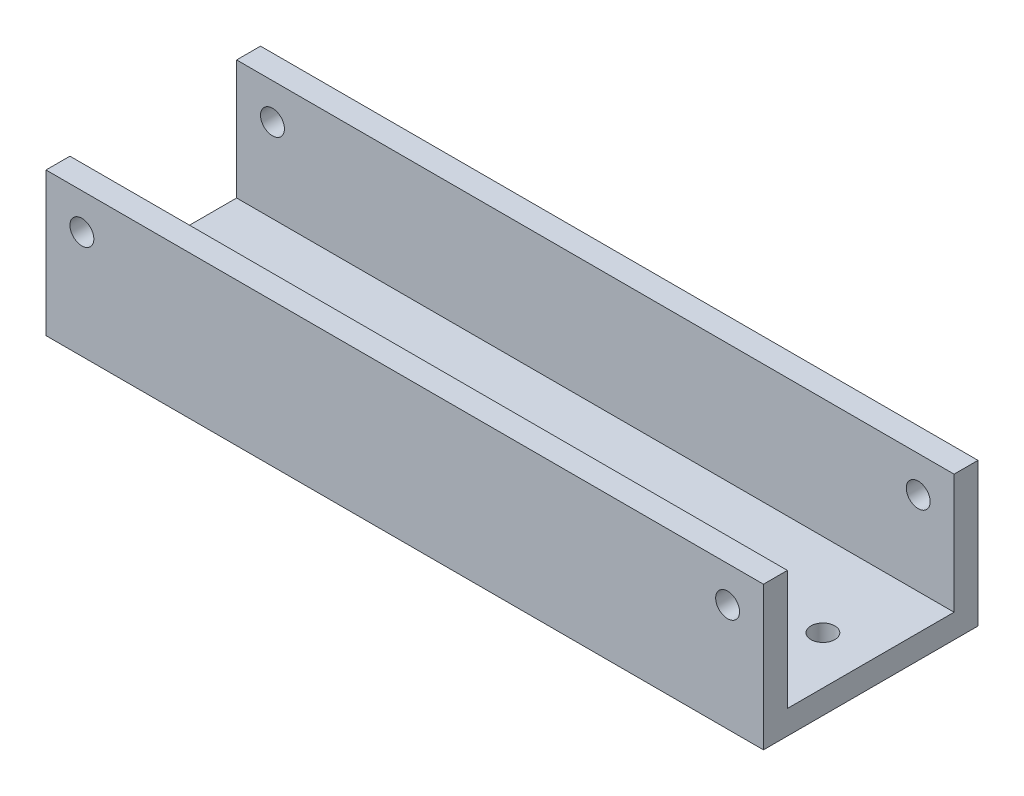
SolidWorks part; units mm, degrees
ref_plane "Front Plane" through (0, 0, 0) normal (0, 0, 1) x (1, 0, 0)
ref_plane "Top Plane" through (0, 0, 0) normal (0, 1, 0) x (1, 0, 0)
ref_plane "Right Plane" through (0, 0, 0) normal (1, 0, 0) x (0, 0, -1)
sketch "Sketch1" plane through (0, 0, 0) normal (0, 1, 0) x (1, 0, 0)
  line L1 (0, 0) -> (-150, 0)
  line L2 (0, 0) -> (0, 40.85)
  line L3 (0, 40.85) -> (-150, 40.85)
  line L4 (-150, 0) -> (-150, 40.85)
  dimension "D1" = 40.85
  dimension "D2" = 150
extrude "Boss-Extrude1" add sketch "Sketch1" along normal blind 3
sketch "Sketch2" plane through (0, 3, 0) normal (0, 1, 0) x (1, 0, 0)
  line L0 (0, 0) -> (0, 40.85) construction
  line L1 (-150, 40.85) -> (0, 40.85)
  line L2 (-150, 40.85) -> (-150, 37.85)
  line L3 (-150, 37.85) -> (0, 37.85)
  line L4 (0, 40.85) -> (0, 37.85)
  line L5 (-150, 40.85) -> (-150, 0) construction
  line L6 (0, 0) -> (-150, 0)
  line L7 (0, 0) -> (0, 3)
  line L8 (0, 3) -> (-150, 3)
  line L9 (-150, 0) -> (-150, 3)
  dimension "D1" = 3
  dimension "D2" = 3
extrude "Boss-Extrude2" add sketch "Sketch2" along normal blind 25
sketch "Sketch5" plane through (0, 0, 0) normal (1, 0, 0) x (0, 0, -1)
  line L0 (3, 28) -> (-2, 28)
  line L1 (-2, 28) -> (-2, -2)
  line L2 (-2, -2) -> (42.85, -2)
  line L3 (42.85, -2) -> (42.85, 28)
  line L4 (42.85, 28) -> (37.85, 28)
  line L5 (37.85, 28) -> (37.85, 3)
  line L6 (37.85, 3) -> (3, 3)
  line L7 (3, 3) -> (3, 28)
  line L8 (3, 3) -> (37.85, 3) construction
  line L9 (37.85, 28) -> (37.85, 3) construction
  dimension "D1" = 5
  dimension "D2" = 5
  dimension "D3" = 5
extrude "Boss-Extrude3" add sketch "Sketch5" against normal up to surface (150 mm away) up to face at (-150, 14.75, -20.425)
sketch "Sketch6" plane through (0, 3, 0) normal (0, 1, 0) x (1, 0, 0)
  line L0 (-150, 37.85) -> (-150, 3) construction
  line L1 (-150, 42.85) -> (0, 42.85) construction
  line L2 (0, 3) -> (0, 37.85) construction
  circle A0 centre (-140, 20.425) radius 2.5
  circle A1 centre (-10, 20.425) radius 2.5
  dimension "D3" = 5
  dimension "D4" = 5
  dimension "D1" = 10
  dimension "D2" = 22.425
  dimension "D5" = 10
  dimension "D6" = 22.425
extrude "Cut-Extrude2" cut sketch "Sketch6" against normal blind 10
sketch "Sketch7" plane through (0, 0, 2) normal (0, 0, 1) x (1, 0, 0)
  line L0 (-150, 28) -> (0, 28) construction
  line L1 (0, 28) -> (0, -2) construction
  line L2 (-150, -2) -> (-150, 28) construction
  circle A0 centre (-142.5, 20.5) radius 2.5
  circle A1 centre (-7.5, 20.5) radius 2.5
  dimension "D1" = 5
  dimension "D2" = 5
  dimension "D3" = 7.5
  dimension "D4" = 7.5
  dimension "D5" = 7.5
  dimension "D6" = 7.5
extrude "Cut-Extrude3" cut sketch "Sketch7" against normal through all
